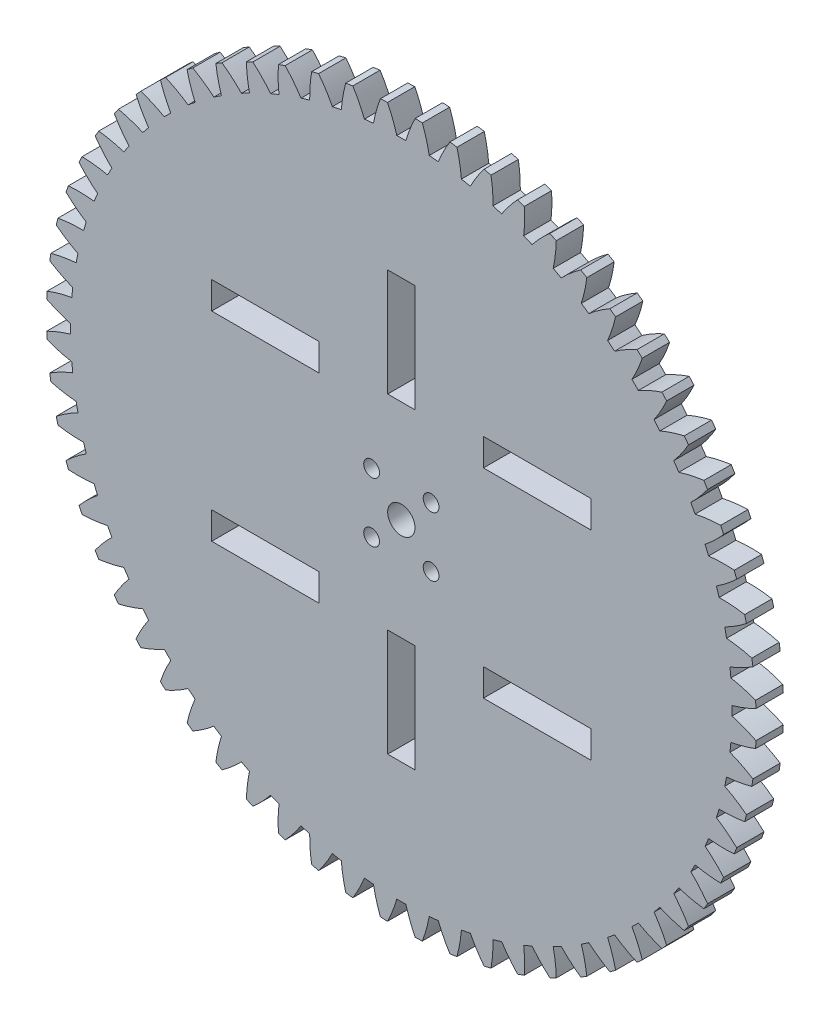
SolidWorks part; units mm, degrees
material "ABS"
ref_plane "Plan de face" through (0, 0, 0) normal (0, 0, 1) x (1, 0, 0)
ref_plane "Plan de dessus" through (0, 0, 0) normal (0, 1, 0) x (1, 0, 0)
ref_plane "Plan de droite" through (0, 0, 0) normal (1, 0, 0) x (0, 0, -1)
sketch "Esquisse1" plane through (0, 0, 0) normal (0, 0, 1) x (1, 0, 0)
  arc A512 (1.0564, -76.8667) -> (3.2229, -82.437) centre (31.8329, -68.1029) ccw
  arc A513 (3.2229, -82.437) -> (4.8728, -82.356) centre (0, 0) ccw
  arc A514 (4.8728, -82.356) -> (6.4829, -76.6002) centre (-25.0044, -70.8951) ccw
  arc A515 (6.4829, -76.6002) -> (8.5856, -76.3931) centre (0, 0) ccw
  arc A516 (8.5856, -76.3931) -> (11.2876, -81.7242) centre (38.3549, -64.6548) ccw
  arc A517 (11.2876, -81.7242) -> (12.9217, -81.4818) centre (0, 0) ccw
  arc A518 (12.9217, -81.4818) -> (13.9598, -75.5959) centre (-17.9351, -73.0046) ccw
  arc A519 (13.9598, -75.5959) -> (16.0321, -75.1837) centre (0, 0) ccw
  arc A520 (16.0321, -75.1837) -> (19.2437, -80.2243) centre (44.5075, -60.584) ccw
  arc A521 (19.2437, -80.2243) -> (20.8461, -79.8229) centre (0, 0) ccw
  arc A522 (20.8461, -79.8229) -> (21.3023, -73.8635) centre (-10.693, -74.411) ccw
  arc A523 (21.3023, -73.8635) -> (23.3242, -73.2502) centre (0, 0) ccw
  arc A524 (23.3242, -73.2502) -> (27.0144, -77.9517) centre (50.2315, -55.9298) ccw
  arc A525 (27.0144, -77.9517) -> (28.5697, -77.3952) centre (0, 0) ccw
  arc A526 (28.5697, -77.3952) -> (28.4396, -71.4199) centre (-3.348, -75.1008) ccw
  arc A527 (28.4396, -71.4199) -> (30.3916, -70.6113) centre (0, 0) ccw
  arc A528 (30.3916, -70.6113) -> (34.5249, -74.9285) centre (55.4717, -50.7369) ccw
  arc A529 (34.5249, -74.9285) -> (36.0182, -74.2222) centre (0, 0) ccw
  arc A530 (36.0182, -74.2222) -> (35.3031, -68.2884) centre (4.0293, -75.0673) ccw
  arc A531 (35.3031, -68.2884) -> (37.1664, -67.2924) centre (0, 0) ccw
  arc A532 (37.1664, -67.2924) -> (41.7029, -71.1837) centre (60.1776, -45.0555) ccw
  arc A533 (41.7029, -71.1837) -> (43.1198, -70.3344) centre (0, 0) ccw
  arc A534 (43.1198, -70.3344) -> (41.8265, -64.4993) centre (11.3678, -74.3109) ccw
  arc A535 (41.8265, -64.4993) -> (43.5832, -63.3255) centre (0, 0) ccw
  arc A536 (43.5832, -63.3255) -> (48.4793, -66.7533) centre (64.3041, -38.9401) ccw
  arc A537 (48.4793, -66.7533) -> (49.8061, -65.7693) centre (0, 0) ccw
  arc A538 (49.8061, -65.7693) -> (47.9471, -60.089) centre (18.5968, -72.8389) ccw
  arc A539 (47.9471, -60.089) -> (49.5804, -58.7486) centre (0, 0) ccw
  arc A540 (49.5804, -58.7486) -> (54.7888, -61.6801) centre (67.8112, -32.4497) ccw
  arc A541 (54.7888, -61.6801) -> (56.0128, -60.5707) centre (0, 0) ccw
  arc A542 (56.0128, -60.5707) -> (53.606, -55.1) centre (25.6467, -70.6653) ccw
  arc A543 (53.606, -55.1) -> (55.1, -53.606) centre (0, 0) ccw
  arc A544 (55.1, -53.606) -> (60.5707, -56.0128) centre (70.6653, -25.6467) ccw
  arc A545 (60.5707, -56.0128) -> (61.6801, -54.7888) centre (0, 0) ccw
  arc A546 (61.6801, -54.7888) -> (58.7486, -49.5804) centre (32.4497, -67.8112) ccw
  arc A547 (58.7486, -49.5804) -> (60.089, -47.9471) centre (0, 0) ccw
  arc A548 (60.089, -47.9471) -> (65.7693, -49.8061) centre (72.8389, -18.5968) ccw
  arc A549 (65.7693, -49.8061) -> (66.7533, -48.4793) centre (0, 0) ccw
  arc A550 (66.7533, -48.4793) -> (63.3255, -43.5832) centre (38.9401, -64.3041) ccw
  arc A551 (63.3255, -43.5832) -> (64.4993, -41.8265) centre (0, 0) ccw
  arc A552 (64.4993, -41.8265) -> (70.3344, -43.1198) centre (74.3109, -11.3678) ccw
  arc A553 (70.3344, -43.1198) -> (71.1837, -41.7029) centre (0, 0) ccw
  arc A554 (71.1837, -41.7029) -> (67.2924, -37.1664) centre (45.0555, -60.1776) ccw
  arc A555 (67.2924, -37.1664) -> (68.2884, -35.3031) centre (0, 0) ccw
  arc A556 (68.2884, -35.3031) -> (74.2222, -36.0182) centre (75.0673, -4.0293) ccw
  arc A557 (74.2222, -36.0182) -> (74.9285, -34.5249) centre (0, 0) ccw
  arc A558 (74.9285, -34.5249) -> (70.6113, -30.3916) centre (50.7369, -55.4717) ccw
  arc A559 (70.6113, -30.3916) -> (71.4199, -28.4396) centre (0, 0) ccw
  arc A560 (71.4199, -28.4396) -> (77.3952, -28.5697) centre (75.1008, 3.348) ccw
  arc A561 (77.3952, -28.5697) -> (77.9517, -27.0144) centre (0, 0) ccw
  arc A562 (77.9517, -27.0144) -> (73.2502, -23.3242) centre (55.9298, -50.2315) ccw
  arc A563 (73.2502, -23.3242) -> (73.8635, -21.3023) centre (0, 0) ccw
  arc A564 (73.8635, -21.3023) -> (79.8229, -20.8461) centre (74.411, 10.693) ccw
  arc A565 (79.8229, -20.8461) -> (80.2243, -19.2437) centre (0, 0) ccw
  arc A566 (80.2243, -19.2437) -> (75.1837, -16.0321) centre (60.584, -44.5075) ccw
  arc A567 (75.1837, -16.0321) -> (75.5959, -13.9598) centre (0, 0) ccw
  arc A568 (75.5959, -13.9598) -> (81.4818, -12.9217) centre (73.0046, 17.9351) ccw
  arc A569 (81.4818, -12.9217) -> (81.7242, -11.2876) centre (0, 0) ccw
  arc A570 (81.7242, -11.2876) -> (76.3931, -8.5856) centre (64.6548, -38.3549) ccw
  arc A571 (76.3931, -8.5856) -> (76.6002, -6.4829) centre (0, 0) ccw
  arc A572 (76.6002, -6.4829) -> (82.356, -4.8728) centre (70.8951, 25.0044) ccw
  arc A573 (82.356, -4.8728) -> (82.437, -3.2229) centre (0, 0) ccw
  arc A574 (82.437, -3.2229) -> (76.8667, -1.0564) centre (68.1029, -31.8329) ccw
  arc A575 (76.8667, -1.0564) -> (76.8667, 1.0564) centre (0, 0) ccw
  arc A576 (76.8667, 1.0564) -> (82.437, 3.2229) centre (68.1029, 31.8329) ccw
  arc A577 (82.437, 3.2229) -> (82.356, 4.8728) centre (0, 0) ccw
  arc A578 (82.356, 4.8728) -> (76.6002, 6.4829) centre (70.8951, -25.0044) ccw
  arc A579 (76.6002, 6.4829) -> (76.3931, 8.5856) centre (0, 0) ccw
  arc A580 (76.3931, 8.5856) -> (81.7242, 11.2876) centre (64.6548, 38.3549) ccw
  arc A581 (81.7242, 11.2876) -> (81.4818, 12.9217) centre (0, 0) ccw
  arc A582 (81.4818, 12.9217) -> (75.5959, 13.9598) centre (73.0046, -17.9351) ccw
  arc A583 (75.5959, 13.9598) -> (75.1837, 16.0321) centre (0, 0) ccw
  arc A584 (75.1837, 16.0321) -> (80.2243, 19.2437) centre (60.584, 44.5075) ccw
  arc A585 (80.2243, 19.2437) -> (79.8229, 20.8461) centre (0, 0) ccw
  arc A586 (79.8229, 20.8461) -> (73.8635, 21.3023) centre (74.411, -10.693) ccw
  arc A587 (73.8635, 21.3023) -> (73.2502, 23.3242) centre (0, 0) ccw
  arc A588 (73.2502, 23.3242) -> (77.9517, 27.0144) centre (55.9298, 50.2315) ccw
  arc A589 (77.9517, 27.0144) -> (77.3952, 28.5697) centre (0, 0) ccw
  arc A590 (77.3952, 28.5697) -> (71.4199, 28.4396) centre (75.1008, -3.348) ccw
  arc A591 (71.4199, 28.4396) -> (70.6113, 30.3916) centre (0, 0) ccw
  arc A592 (70.6113, 30.3916) -> (74.9285, 34.5249) centre (50.7369, 55.4717) ccw
  arc A593 (74.9285, 34.5249) -> (74.2222, 36.0182) centre (0, 0) ccw
  arc A594 (74.2222, 36.0182) -> (68.2884, 35.3031) centre (75.0673, 4.0293) ccw
  arc A595 (68.2884, 35.3031) -> (67.2924, 37.1664) centre (0, 0) ccw
  arc A596 (67.2924, 37.1664) -> (71.1837, 41.7029) centre (45.0555, 60.1776) ccw
  arc A597 (71.1837, 41.7029) -> (70.3344, 43.1198) centre (0, 0) ccw
  arc A598 (70.3344, 43.1198) -> (64.4993, 41.8265) centre (74.3109, 11.3678) ccw
  arc A599 (64.4993, 41.8265) -> (63.3255, 43.5832) centre (0, 0) ccw
  arc A600 (63.3255, 43.5832) -> (66.7533, 48.4793) centre (38.9401, 64.3041) ccw
  arc A601 (66.7533, 48.4793) -> (65.7693, 49.8061) centre (0, 0) ccw
  arc A602 (65.7693, 49.8061) -> (60.089, 47.9471) centre (72.8389, 18.5968) ccw
  arc A603 (60.089, 47.9471) -> (58.7486, 49.5804) centre (0, 0) ccw
  arc A604 (58.7486, 49.5804) -> (61.6801, 54.7888) centre (32.4497, 67.8112) ccw
  arc A605 (61.6801, 54.7888) -> (60.5707, 56.0128) centre (0, 0) ccw
  arc A606 (60.5707, 56.0128) -> (55.1, 53.606) centre (70.6653, 25.6467) ccw
  arc A607 (55.1, 53.606) -> (53.606, 55.1) centre (0, 0) ccw
  arc A608 (53.606, 55.1) -> (56.0128, 60.5707) centre (25.6467, 70.6653) ccw
  arc A609 (56.0128, 60.5707) -> (54.7888, 61.6801) centre (0, 0) ccw
  arc A610 (54.7888, 61.6801) -> (49.5804, 58.7486) centre (67.8112, 32.4497) ccw
  arc A611 (49.5804, 58.7486) -> (47.9471, 60.089) centre (0, 0) ccw
  arc A612 (47.9471, 60.089) -> (49.8061, 65.7693) centre (18.5968, 72.8389) ccw
  arc A613 (49.8061, 65.7693) -> (48.4793, 66.7533) centre (0, 0) ccw
  arc A614 (48.4793, 66.7533) -> (43.5832, 63.3255) centre (64.3041, 38.9401) ccw
  arc A615 (43.5832, 63.3255) -> (41.8265, 64.4993) centre (0, 0) ccw
  arc A616 (41.8265, 64.4993) -> (43.1198, 70.3344) centre (11.3678, 74.3109) ccw
  arc A617 (43.1198, 70.3344) -> (41.7029, 71.1837) centre (0, 0) ccw
  arc A618 (41.7029, 71.1837) -> (37.1664, 67.2924) centre (60.1776, 45.0555) ccw
  arc A619 (37.1664, 67.2924) -> (35.3031, 68.2884) centre (0, 0) ccw
  arc A620 (35.3031, 68.2884) -> (36.0182, 74.2222) centre (4.0293, 75.0673) ccw
  arc A621 (36.0182, 74.2222) -> (34.5249, 74.9285) centre (0, 0) ccw
  arc A622 (34.5249, 74.9285) -> (30.3916, 70.6113) centre (55.4717, 50.7369) ccw
  arc A623 (30.3916, 70.6113) -> (28.4396, 71.4199) centre (0, 0) ccw
  arc A624 (28.4396, 71.4199) -> (28.5697, 77.3952) centre (-3.348, 75.1008) ccw
  arc A625 (28.5697, 77.3952) -> (27.0144, 77.9517) centre (0, 0) ccw
  arc A626 (27.0144, 77.9517) -> (23.3242, 73.2502) centre (50.2315, 55.9298) ccw
  arc A627 (23.3242, 73.2502) -> (21.3023, 73.8635) centre (0, 0) ccw
  arc A628 (21.3023, 73.8635) -> (20.8461, 79.8229) centre (-10.693, 74.411) ccw
  arc A629 (20.8461, 79.8229) -> (19.2437, 80.2243) centre (0, 0) ccw
  arc A630 (19.2437, 80.2243) -> (16.0321, 75.1837) centre (44.5075, 60.584) ccw
  arc A631 (16.0321, 75.1837) -> (13.9598, 75.5959) centre (0, 0) ccw
  arc A632 (13.9598, 75.5959) -> (12.9217, 81.4818) centre (-17.9351, 73.0046) ccw
  arc A633 (12.9217, 81.4818) -> (11.2876, 81.7242) centre (0, 0) ccw
  arc A634 (11.2876, 81.7242) -> (8.5856, 76.3931) centre (38.3549, 64.6548) ccw
  arc A635 (8.5856, 76.3931) -> (6.4829, 76.6002) centre (0, 0) ccw
  arc A636 (6.4829, 76.6002) -> (4.8728, 82.356) centre (-25.0044, 70.8951) ccw
  arc A637 (4.8728, 82.356) -> (3.2229, 82.437) centre (0, 0) ccw
  arc A638 (3.2229, 82.437) -> (1.0564, 76.8667) centre (31.8329, 68.1029) ccw
  arc A639 (1.0564, 76.8667) -> (-1.0564, 76.8667) centre (0, 0) ccw
  arc A640 (-1.0564, 76.8667) -> (-3.2229, 82.437) centre (-31.8329, 68.1029) ccw
  arc A641 (-3.2229, 82.437) -> (-4.8728, 82.356) centre (0, 0) ccw
  arc A642 (-4.8728, 82.356) -> (-6.4829, 76.6002) centre (25.0044, 70.8951) ccw
  arc A643 (-6.4829, 76.6002) -> (-8.5856, 76.3931) centre (0, 0) ccw
  arc A644 (-8.5856, 76.3931) -> (-11.2876, 81.7242) centre (-38.3549, 64.6548) ccw
  arc A645 (-11.2876, 81.7242) -> (-12.9217, 81.4818) centre (0, 0) ccw
  arc A646 (-12.9217, 81.4818) -> (-13.9598, 75.5959) centre (17.9351, 73.0046) ccw
  arc A647 (-13.9598, 75.5959) -> (-16.0321, 75.1837) centre (0, 0) ccw
  arc A648 (-16.0321, 75.1837) -> (-19.2437, 80.2243) centre (-44.5075, 60.584) ccw
  arc A649 (-19.2437, 80.2243) -> (-20.8461, 79.8229) centre (0, 0) ccw
  arc A650 (-20.8461, 79.8229) -> (-21.3023, 73.8635) centre (10.693, 74.411) ccw
  arc A651 (-21.3023, 73.8635) -> (-23.3242, 73.2502) centre (0, 0) ccw
  arc A652 (-23.3242, 73.2502) -> (-27.0144, 77.9517) centre (-50.2315, 55.9298) ccw
  arc A653 (-27.0144, 77.9517) -> (-28.5697, 77.3952) centre (0, 0) ccw
  arc A654 (-28.5697, 77.3952) -> (-28.4396, 71.4199) centre (3.348, 75.1008) ccw
  arc A655 (-28.4396, 71.4199) -> (-30.3916, 70.6113) centre (0, 0) ccw
  arc A656 (-30.3916, 70.6113) -> (-34.5249, 74.9285) centre (-55.4717, 50.7369) ccw
  arc A657 (-34.5249, 74.9285) -> (-36.0182, 74.2222) centre (0, 0) ccw
  arc A658 (-36.0182, 74.2222) -> (-35.3031, 68.2884) centre (-4.0293, 75.0673) ccw
  arc A659 (-35.3031, 68.2884) -> (-37.1664, 67.2924) centre (0, 0) ccw
  arc A660 (-37.1664, 67.2924) -> (-41.7029, 71.1837) centre (-60.1776, 45.0555) ccw
  arc A661 (-41.7029, 71.1837) -> (-43.1198, 70.3344) centre (0, 0) ccw
  arc A662 (-43.1198, 70.3344) -> (-41.8265, 64.4993) centre (-11.3678, 74.3109) ccw
  arc A663 (-41.8265, 64.4993) -> (-43.5832, 63.3255) centre (0, 0) ccw
  arc A664 (-43.5832, 63.3255) -> (-48.4793, 66.7533) centre (-64.3041, 38.9401) ccw
  arc A665 (-48.4793, 66.7533) -> (-49.8061, 65.7693) centre (0, 0) ccw
  arc A666 (-49.8061, 65.7693) -> (-47.9471, 60.089) centre (-18.5968, 72.8389) ccw
  arc A667 (-47.9471, 60.089) -> (-49.5804, 58.7486) centre (0, 0) ccw
  arc A668 (-49.5804, 58.7486) -> (-54.7888, 61.6801) centre (-67.8112, 32.4497) ccw
  arc A669 (-54.7888, 61.6801) -> (-56.0128, 60.5707) centre (0, 0) ccw
  arc A670 (-56.0128, 60.5707) -> (-53.606, 55.1) centre (-25.6467, 70.6653) ccw
  arc A671 (-53.606, 55.1) -> (-55.1, 53.606) centre (0, 0) ccw
  arc A672 (-55.1, 53.606) -> (-60.5707, 56.0128) centre (-70.6653, 25.6467) ccw
  arc A673 (-60.5707, 56.0128) -> (-61.6801, 54.7888) centre (0, 0) ccw
  arc A674 (-61.6801, 54.7888) -> (-58.7486, 49.5804) centre (-32.4497, 67.8112) ccw
  arc A675 (-58.7486, 49.5804) -> (-60.089, 47.9471) centre (0, 0) ccw
  arc A676 (-60.089, 47.9471) -> (-65.7693, 49.8061) centre (-72.8389, 18.5968) ccw
  arc A677 (-65.7693, 49.8061) -> (-66.7533, 48.4793) centre (0, 0) ccw
  arc A678 (-66.7533, 48.4793) -> (-63.3255, 43.5832) centre (-38.9401, 64.3041) ccw
  arc A679 (-63.3255, 43.5832) -> (-64.4993, 41.8265) centre (0, 0) ccw
  arc A680 (-64.4993, 41.8265) -> (-70.3344, 43.1198) centre (-74.3109, 11.3678) ccw
  arc A681 (-70.3344, 43.1198) -> (-71.1837, 41.7029) centre (0, 0) ccw
  arc A682 (-71.1837, 41.7029) -> (-67.2924, 37.1664) centre (-45.0555, 60.1776) ccw
  arc A683 (-67.2924, 37.1664) -> (-68.2884, 35.3031) centre (0, 0) ccw
  arc A684 (-68.2884, 35.3031) -> (-74.2222, 36.0182) centre (-75.0673, 4.0293) ccw
  arc A685 (-74.2222, 36.0182) -> (-74.9285, 34.5249) centre (0, 0) ccw
  arc A686 (-74.9285, 34.5249) -> (-70.6113, 30.3916) centre (-50.7369, 55.4717) ccw
  arc A687 (-70.6113, 30.3916) -> (-71.4199, 28.4396) centre (0, 0) ccw
  arc A688 (-71.4199, 28.4396) -> (-77.3952, 28.5697) centre (-75.1008, -3.348) ccw
  arc A689 (-77.3952, 28.5697) -> (-77.9517, 27.0144) centre (0, 0) ccw
  arc A690 (-77.9517, 27.0144) -> (-73.2502, 23.3242) centre (-55.9298, 50.2315) ccw
  arc A691 (-73.2502, 23.3242) -> (-73.8635, 21.3023) centre (0, 0) ccw
  arc A692 (-73.8635, 21.3023) -> (-79.8229, 20.8461) centre (-74.411, -10.693) ccw
  arc A693 (-79.8229, 20.8461) -> (-80.2243, 19.2437) centre (0, 0) ccw
  arc A694 (-80.2243, 19.2437) -> (-75.1837, 16.0321) centre (-60.584, 44.5075) ccw
  arc A695 (-75.1837, 16.0321) -> (-75.5959, 13.9598) centre (0, 0) ccw
  arc A696 (-75.5959, 13.9598) -> (-81.4818, 12.9217) centre (-73.0046, -17.9351) ccw
  arc A697 (-81.4818, 12.9217) -> (-81.7242, 11.2876) centre (0, 0) ccw
  arc A698 (-81.7242, 11.2876) -> (-76.3931, 8.5856) centre (-64.6548, 38.3549) ccw
  arc A699 (-76.3931, 8.5856) -> (-76.6002, 6.4829) centre (0, 0) ccw
  arc A700 (-76.6002, 6.4829) -> (-82.356, 4.8728) centre (-70.8951, -25.0044) ccw
  arc A701 (-82.356, 4.8728) -> (-82.437, 3.2229) centre (0, 0) ccw
  arc A702 (-82.437, 3.2229) -> (-76.8667, 1.0564) centre (-68.1029, 31.8329) ccw
  arc A703 (-76.8667, 1.0564) -> (-76.8667, -1.0564) centre (0, 0) ccw
  arc A704 (-76.8667, -1.0564) -> (-82.437, -3.2229) centre (-68.1029, -31.8329) ccw
  arc A705 (-82.437, -3.2229) -> (-82.356, -4.8728) centre (0, 0) ccw
  arc A706 (-82.356, -4.8728) -> (-76.6002, -6.4829) centre (-70.8951, 25.0044) ccw
  arc A707 (-76.6002, -6.4829) -> (-76.3931, -8.5856) centre (0, 0) ccw
  arc A708 (-76.3931, -8.5856) -> (-81.7242, -11.2876) centre (-64.6548, -38.3549) ccw
  arc A709 (-81.7242, -11.2876) -> (-81.4818, -12.9217) centre (0, 0) ccw
  arc A710 (-81.4818, -12.9217) -> (-75.5959, -13.9598) centre (-73.0046, 17.9351) ccw
  arc A711 (-75.5959, -13.9598) -> (-75.1837, -16.0321) centre (0, 0) ccw
  arc A712 (-75.1837, -16.0321) -> (-80.2243, -19.2437) centre (-60.584, -44.5075) ccw
  arc A713 (-80.2243, -19.2437) -> (-79.8229, -20.8461) centre (0, 0) ccw
  arc A714 (-79.8229, -20.8461) -> (-73.8635, -21.3023) centre (-74.411, 10.693) ccw
  arc A715 (-73.8635, -21.3023) -> (-73.2502, -23.3242) centre (0, 0) ccw
  arc A716 (-73.2502, -23.3242) -> (-77.9517, -27.0144) centre (-55.9298, -50.2315) ccw
  arc A717 (-77.9517, -27.0144) -> (-77.3952, -28.5697) centre (0, 0) ccw
  arc A718 (-77.3952, -28.5697) -> (-71.4199, -28.4396) centre (-75.1008, 3.348) ccw
  arc A719 (-71.4199, -28.4396) -> (-70.6113, -30.3916) centre (0, 0) ccw
  arc A720 (-70.6113, -30.3916) -> (-74.9285, -34.5249) centre (-50.7369, -55.4717) ccw
  arc A721 (-74.9285, -34.5249) -> (-74.2222, -36.0182) centre (0, 0) ccw
  arc A722 (-74.2222, -36.0182) -> (-68.2884, -35.3031) centre (-75.0673, -4.0293) ccw
  arc A723 (-68.2884, -35.3031) -> (-67.2924, -37.1664) centre (0, 0) ccw
  arc A724 (-67.2924, -37.1664) -> (-71.1837, -41.7029) centre (-45.0555, -60.1776) ccw
  arc A725 (-71.1837, -41.7029) -> (-70.3344, -43.1198) centre (0, 0) ccw
  arc A726 (-70.3344, -43.1198) -> (-64.4993, -41.8265) centre (-74.3109, -11.3678) ccw
  arc A727 (-64.4993, -41.8265) -> (-63.3255, -43.5832) centre (0, 0) ccw
  arc A728 (-63.3255, -43.5832) -> (-66.7533, -48.4793) centre (-38.9401, -64.3041) ccw
  arc A729 (-66.7533, -48.4793) -> (-65.7693, -49.8061) centre (0, 0) ccw
  arc A730 (-65.7693, -49.8061) -> (-60.089, -47.9471) centre (-72.8389, -18.5968) ccw
  arc A731 (-60.089, -47.9471) -> (-58.7486, -49.5804) centre (0, 0) ccw
  arc A732 (-58.7486, -49.5804) -> (-61.6801, -54.7888) centre (-32.4497, -67.8112) ccw
  arc A733 (-61.6801, -54.7888) -> (-60.5707, -56.0128) centre (0, 0) ccw
  arc A734 (-60.5707, -56.0128) -> (-55.1, -53.606) centre (-70.6653, -25.6467) ccw
  arc A735 (-55.1, -53.606) -> (-53.606, -55.1) centre (0, 0) ccw
  arc A736 (-53.606, -55.1) -> (-56.0128, -60.5707) centre (-25.6467, -70.6653) ccw
  arc A737 (-56.0128, -60.5707) -> (-54.7888, -61.6801) centre (0, 0) ccw
  arc A738 (-54.7888, -61.6801) -> (-49.5804, -58.7486) centre (-67.8112, -32.4497) ccw
  arc A739 (-49.5804, -58.7486) -> (-47.9471, -60.089) centre (0, 0) ccw
  arc A740 (-47.9471, -60.089) -> (-49.8061, -65.7693) centre (-18.5968, -72.8389) ccw
  arc A741 (-49.8061, -65.7693) -> (-48.4793, -66.7533) centre (0, 0) ccw
  arc A742 (-48.4793, -66.7533) -> (-43.5832, -63.3255) centre (-64.3041, -38.9401) ccw
  arc A743 (-43.5832, -63.3255) -> (-41.8265, -64.4993) centre (0, 0) ccw
  arc A744 (-41.8265, -64.4993) -> (-43.1198, -70.3344) centre (-11.3678, -74.3109) ccw
  arc A745 (-43.1198, -70.3344) -> (-41.7029, -71.1837) centre (0, 0) ccw
  arc A746 (-41.7029, -71.1837) -> (-37.1664, -67.2924) centre (-60.1776, -45.0555) ccw
  arc A747 (-37.1664, -67.2924) -> (-35.3031, -68.2884) centre (0, 0) ccw
  arc A748 (-35.3031, -68.2884) -> (-36.0182, -74.2222) centre (-4.0293, -75.0673) ccw
  arc A749 (-36.0182, -74.2222) -> (-34.5249, -74.9285) centre (0, 0) ccw
  arc A750 (-34.5249, -74.9285) -> (-30.3916, -70.6113) centre (-55.4717, -50.7369) ccw
  arc A751 (-30.3916, -70.6113) -> (-28.4396, -71.4199) centre (0, 0) ccw
  arc A752 (-28.4396, -71.4199) -> (-28.5697, -77.3952) centre (3.348, -75.1008) ccw
  arc A753 (-28.5697, -77.3952) -> (-27.0144, -77.9517) centre (0, 0) ccw
  arc A754 (-27.0144, -77.9517) -> (-23.3242, -73.2502) centre (-50.2315, -55.9298) ccw
  arc A755 (-23.3242, -73.2502) -> (-21.3023, -73.8635) centre (0, 0) ccw
  arc A756 (-21.3023, -73.8635) -> (-20.8461, -79.8229) centre (10.693, -74.411) ccw
  arc A757 (-20.8461, -79.8229) -> (-19.2437, -80.2243) centre (0, 0) ccw
  arc A758 (-19.2437, -80.2243) -> (-16.0321, -75.1837) centre (-44.5075, -60.584) ccw
  arc A759 (-16.0321, -75.1837) -> (-13.9598, -75.5959) centre (0, 0) ccw
  arc A760 (-13.9598, -75.5959) -> (-12.9217, -81.4818) centre (17.9351, -73.0046) ccw
  arc A761 (-12.9217, -81.4818) -> (-11.2876, -81.7242) centre (0, 0) ccw
  arc A762 (-11.2876, -81.7242) -> (-8.5856, -76.3931) centre (-38.3549, -64.6548) ccw
  arc A763 (-8.5856, -76.3931) -> (-6.4829, -76.6002) centre (0, 0) ccw
  arc A764 (-6.4829, -76.6002) -> (-4.8728, -82.356) centre (25.0044, -70.8951) ccw
  arc A765 (-4.8728, -82.356) -> (-3.2229, -82.437) centre (0, 0) ccw
  arc A766 (-3.2229, -82.437) -> (-1.0564, -76.8667) centre (-31.8329, -68.1029) ccw
  arc A767 (-1.0564, -76.8667) -> (1.0564, -76.8667) centre (0, 0) ccw
extrude "Boss.-Extru.1" add sketch "Esquisse1" along normal mid plane 6.35
sketch "Esquisse3" plane through (0, 0, 3.175) normal (0, 0, 1) x (1, 0, 0)
  circle A0 centre (0, 0) radius 3.175
  circle A1 centre (-6.9148, -6.9148) radius 1.83
  arc A3 (-6.9148, -8.6674) -> (-6.7103, -5.1742) centre (-6.9148, -6.9148) ccw construction
  arc A4 (0, -3.175) -> (0, 3.175) centre (0, 0) ccw construction
  circle A5 centre (-6.9148, 6.9148) radius 1.83
  circle A6 centre (6.9148, 6.9148) radius 1.83
  circle A7 centre (6.9148, -6.9148) radius 1.83
  point P20 (0, 0)
  dimension "D1" = 3.66
  dimension "D2" = 4
extrude "Enlèv. mat.-Extru.1" cut sketch "Esquisse3" against normal up to next
ref_plane "Plane1" through (-58.7486, 49.5804, 3.175) normal (0, 0, -1) x (-1, 0, 0)
sketch "Sketch1" plane through (-58.7486, 49.5804, 3.175) normal (0, 0, -1) x (-1, 0, 0)
  line L1 (-77.8361, -69.5804) -> (-102.8361, -69.5804)
  line L2 (-77.8361, -69.5804) -> (-77.8361, -75.9304)
  line L3 (-77.8361, -75.9304) -> (-102.8361, -75.9304)
  line L4 (-102.8361, -69.5804) -> (-102.8361, -75.9304)
  line L5 (-77.8361, -23.2304) -> (-102.8361, -23.2304)
  line L6 (-77.8361, -23.2304) -> (-77.8361, -29.5804)
  line L7 (-77.8361, -29.5804) -> (-102.8361, -29.5804)
  line L8 (-102.8361, -23.2304) -> (-102.8361, -29.5804)
  line L9 (-61.9236, -98.3304) -> (-55.5736, -98.3304)
  line L10 (-61.9236, -98.3304) -> (-61.9236, -73.3304)
  line L11 (-61.9236, -73.3304) -> (-55.5736, -73.3304)
  line L12 (-55.5736, -98.3304) -> (-55.5736, -73.3304)
  line L13 (-55.5736, -25.8304) -> (-61.9236, -25.8304)
  line L14 (-55.5736, -25.8304) -> (-55.5736, -0.8304)
  line L15 (-55.5736, -0.8304) -> (-61.9236, -0.8304)
  line L16 (-61.9236, -25.8304) -> (-61.9236, -0.8304)
  line L17 (-14.6611, -23.2304) -> (-39.6611, -23.2304)
  line L18 (-14.6611, -23.2304) -> (-14.6611, -29.5804)
  line L19 (-14.6611, -29.5804) -> (-39.6611, -29.5804)
  line L20 (-39.6611, -23.2304) -> (-39.6611, -29.5804)
  line L21 (-14.6611, -69.5804) -> (-39.6611, -69.5804)
  line L22 (-14.6611, -69.5804) -> (-14.6611, -75.9304)
  line L23 (-14.6611, -75.9304) -> (-39.6611, -75.9304)
  line L24 (-39.6611, -69.5804) -> (-39.6611, -75.9304)
extrude "Cut-Extrude1" cut sketch "Sketch1" along normal through all
